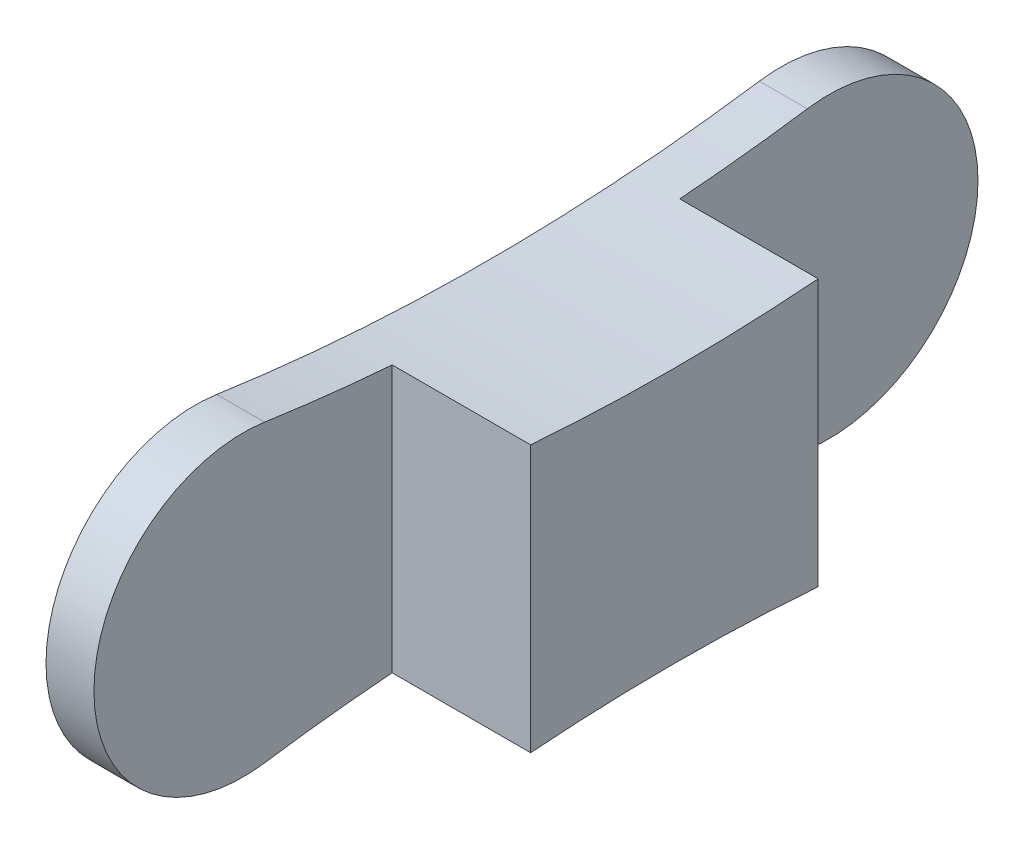
SolidWorks part; units mm, degrees
ref_plane "Front Plane" through (0, 0, 0) normal (0, 0, 1) x (1, 0, 0)
ref_plane "Top Plane" through (0, 0, 0) normal (0, 1, 0) x (1, 0, 0)
ref_plane "Right Plane" through (0, 0, 0) normal (1, 0, 0) x (0, 0, -1)
sketch "Sketch1" plane through (0, 0, 0) normal (1, 0, 0) x (0, 0, -1)
  line L0 (-188.563, 0) -> (207.6309, 0) construction
  circle A0 centre (-110, 0) radius 28
  circle A1 centre (0, 0) radius 28
  arc A2 (-105.9487, 27.7054) -> (-4.0513, 27.7054) centre (-55, 376.125) ccw
  arc A3 (-105.9487, -27.7054) -> (-4.0513, -27.7054) centre (-55, -376.125) cw
  point P13 (-55, 24)
  point P14 (-55, -24)
  dimension "D1" = 56
  dimension "D2" = 56
  dimension "D3" = 110
  dimension "D4" = 48
extrude "Boss-Extrude1" add sketch "Sketch1" along normal blind 35 contours A1 L0 | L0 A1 | A0 L0 A1 A2 | L0 A0 A3 A1 | L0 A0 | A0 L0
sketch "Sketch4" plane through (0, 0, 0) normal (0, 1, 0) x (1, 0, 0)
  line L0 (-64.695, -55) -> (222.9919, -55) construction
  line L1 (9, 28) -> (61, 28)
  line L2 (9, 28) -> (9, -28)
  line L3 (9, -28) -> (61, -28)
  line L4 (61, 28) -> (61, -28)
  line L5 (9, 28) -> (61, -28) construction
  line L6 (9, -28) -> (61, 28) construction
  line L7 (9, -82) -> (61, -138) construction
  line L8 (9, -138) -> (61, -82) construction
  line L9 (61, -138) -> (61, -82)
  line L10 (9, -82) -> (61, -82)
  line L11 (9, -138) -> (9, -82)
  line L12 (9, -138) -> (61, -138)
  point P0 (35, 0)
  point P12 (35, -110)
  dimension "D1" = 56
  dimension "D2" = 52
  dimension "D3" = 35
  dimension "D4" = 55
extrude "Cut-Extrude1" cut sketch "Sketch4" against normal through all both and the other way through all
sketch "Sketch5" plane through (0, 0, 0) normal (1, 0, 0) x (0, 0, -1)
  line L1 (-30.5, -15.5) -> (-61.5, -15.5) construction
  line L2 (-30.5, -15.5) -> (-30.5, 15.5) construction
  line L3 (-30.5, 15.5) -> (-61.5, 15.5) construction
  line L4 (-61.5, -15.5) -> (-61.5, 15.5) construction
  line L5 (-30.5, -15.5) -> (-61.5, 15.5) construction
  line L6 (-30.5, 15.5) -> (-61.5, -15.5) construction
  circle A8 centre (-30.5, -15.5) radius 1.6
  circle A9 centre (-30.5, 15.5) radius 1.6
  circle A10 centre (-61.5, -15.5) radius 1.6
  circle A11 centre (-61.5, 15.5) radius 1.6
  circle A12 centre (-30.5, -15.5) radius 3
  circle A13 centre (-30.5, 15.5) radius 3
  circle A14 centre (-61.5, -15.5) radius 3
  circle A15 centre (-61.5, 15.5) radius 3
  point P0 (-46, 0)
  dimension "D4" = 3.2
  dimension "D5" = 6
  dimension "D1" = 46
  dimension "D2" = 31
  dimension "D3" = 31
sketch "Sketch6" plane through (0, 0, 0) normal (1, 0, 0) x (0, 0, -1)
  line L1 (-24.9, -21.1) -> (-67.1, -21.1)
  line L2 (-24.9, -21.1) -> (-24.9, 21.1)
  line L3 (-24.9, 21.1) -> (-67.1, 21.1)
  line L4 (-67.1, -21.1) -> (-67.1, 21.1)
  line L5 (-24.9, -21.1) -> (-67.1, 21.1) construction
  line L6 (-24.9, 21.1) -> (-67.1, -21.1) construction
  point P0 (-46, 0)
  dimension "D1" = 46
  dimension "D2" = 42.2
  dimension "D3" = 42.2
sketch "Sketch7" plane through (0, 0, 0) normal (1, 0, 0) x (0, 0, -1)
  circle A0 centre (0, 0) radius 4.1
  circle A1 centre (-110, 0) radius 4.1
  circle A2 centre (0, 0) radius 11.1
  circle A3 centre (-110, 0) radius 11.1
  dimension "D3" = 110
  dimension "D1" = 8.2
  dimension "D2" = 22.2
ref_plane "Plane1" through (35, 0, 0) normal (1, 0, 0) x (0, 0, -1)
equation "\"top dia\"= 56"
equation "\"D1@Sketch1\"=\"top dia\""
equation "\"bottom dia\"= 56"
equation "\"D2@Sketch1\"=\"bottom dia\""
equation "\"arm length\"= 110"
equation "\"D3@Sketch1\"=\"arm length\""
equation "\"across\"= 48"
equation "\"D4@Sketch1\"=\"across\""
equation "\"arm width\"=70"
equation "\"D1@Boss-Extrude1\"=\"arm width\"/2"
equation "\"D1@Sketch4\"=\"bottom dia\""
equation "\"D2@Sketch4\"=\"arm width\" - (7+2)*2"
equation "\"D3@Sketch4\"=\"arm width\"/2"
equation "\"D4@Sketch4\"=\"arm length\"/2"
equation "\"gear dist\"=46"
equation "\"D1@Sketch5\"=\"gear dist\""
equation "\"D1@Sketch6\"=\"gear dist\""
equation "\"D3@Sketch7\"=\"arm length\" "
equation "\"D1@Plane1\"= \"arm width\" / 2"
